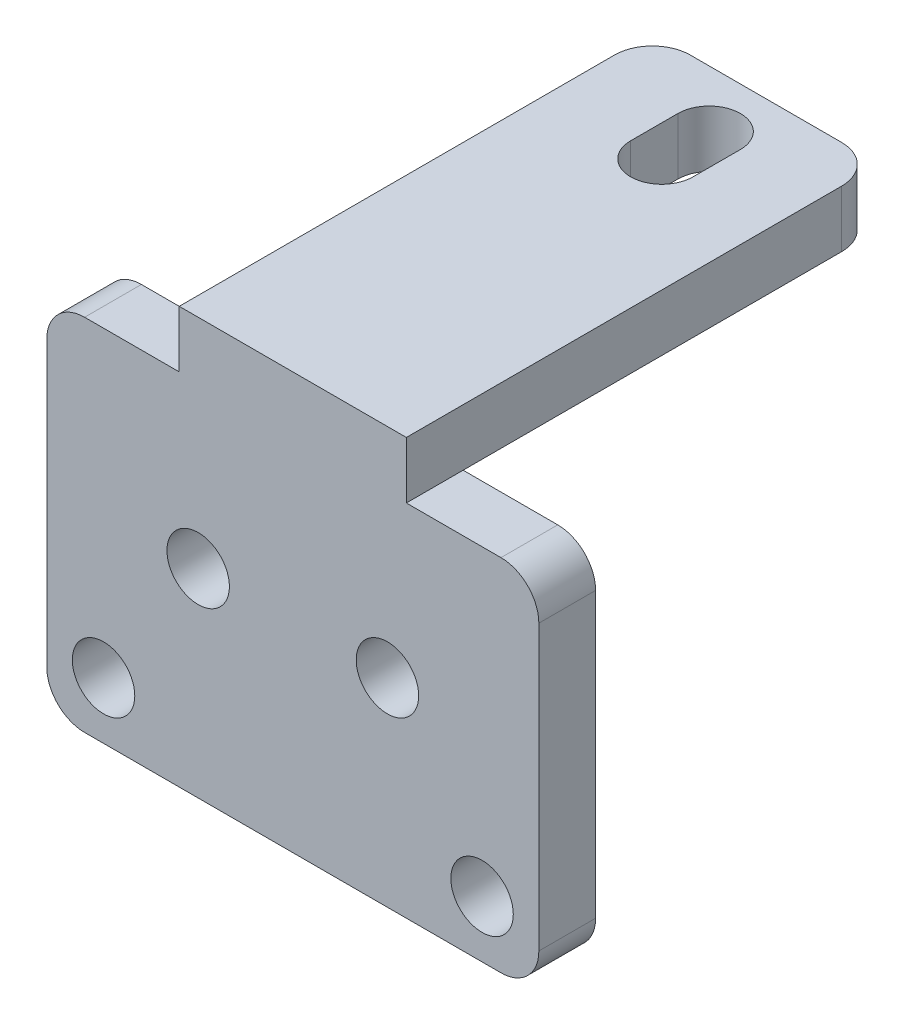
SolidWorks part; units mm, degrees
ref_plane "前视基准面" through (0, 0, 0) normal (0, 0, 1) x (1, 0, 0)
ref_plane "上视基准面" through (0, 0, 0) normal (0, 1, 0) x (1, 0, 0)
ref_plane "右视基准面" through (0, 0, 0) normal (1, 0, 0) x (0, 0, -1)
sketch "草图1" plane through (0, 0, 0) normal (0, 0, 1) x (1, 0, 0)
  line L0 (-13, 19) -> (-13, -3)
  line L1 (-13, 19) -> (13, 19)
  line L2 (-13, -3) -> (13, -3)
  line L3 (13, 19) -> (13, -3)
  line L4 (13, 16) -> (-13, 16)
  line L5 (-6, 16) -> (-6, 19)
  line L6 (6, 16) -> (6, 19)
  line L25 (0, 0) -> (-10, 0)
  line L29 (0, 0) -> (10, 0)
  circle A6 centre (-5, 7.5) radius 1.65
  circle A13 centre (5, 7.5) radius 1.65
  circle A32 centre (-10, 0) radius 1.65
  circle A33 centre (10, 0) radius 1.65
extrude "凸台-拉伸1" add sketch "草图1" along normal blind 3
sketch "草图2" plane through (0, 0, 0) normal (0, 0, -1) x (-1, 0, 0)
  line L0 (6, 19) -> (-6, 19)
  line L3 (13, 16) -> (-13, 16)
  line L4 (-6, 19) -> (-6, 16)
  line L5 (-6, 16) -> (6, 16)
  line L6 (6, 16) -> (6, 19)
extrude "凸台-拉伸2" add sketch "草图2" along normal blind 22
sketch "草图4" plane through (0, 0, 0) normal (0, 1, 0) x (1, 0, 0)
  line L0 (-6, 22) -> (6, 22)
  line L1 (-6, 22) -> (-6, 0)
  line L2 (6, 22) -> (6, 0)
  line L3 (-6, 0) -> (6, 0)
  line L4 (0, 0) -> (0, 19)
  line L5 (0, 0) -> (0, 16.5)
  line L6 (1.65, 16.5) -> (1.65, 19)
  line L7 (-1.65, 16.5) -> (-1.65, 19)
  circle A0 centre (0, 19) radius 1.65
  circle A1 centre (0, 16.5) radius 1.65
extrude "切除-拉伸2" cut sketch "草图4" along normal blind 32
fillet "圆角1" radius 2 6 edges at (-6, 17.5, -22) (6, 17.5, -22) (-13, 16, 1.5) (13, 16, 1.5) (13, -3, 1.5) (-13, -3, 1.5)
